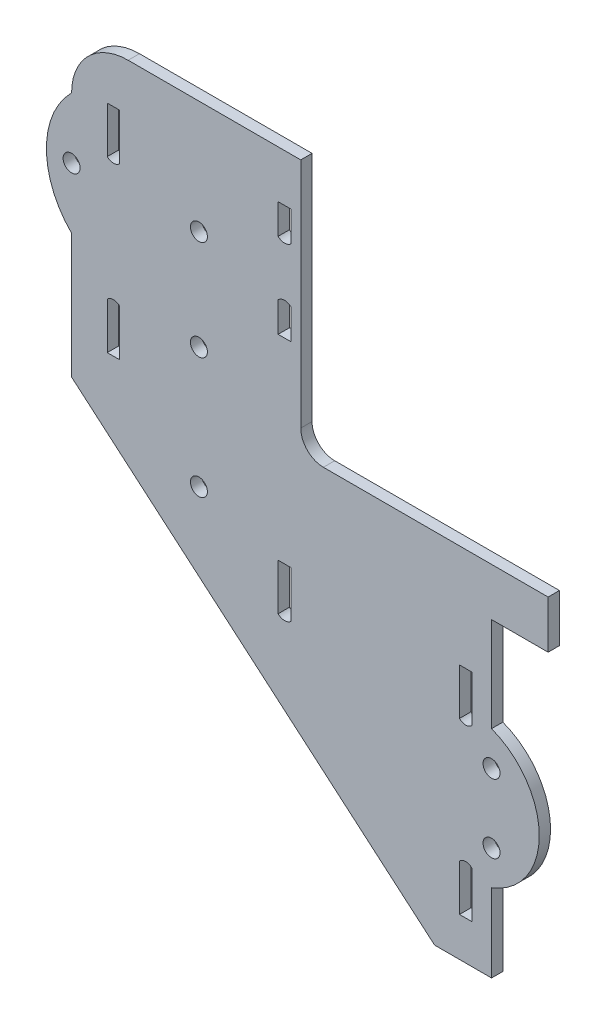
SolidWorks part; units mm, degrees
ref_plane "前视基准面" through (0, 0, 0) normal (0, 0, 1) x (1, 0, 0)
ref_plane "上视基准面" through (0, 0, 0) normal (0, 1, 0) x (1, 0, 0)
ref_plane "右视基准面" through (0, 0, 0) normal (1, 0, 0) x (0, 0, -1)
sketch "草图1" plane through (0, 0, 0) normal (0, 0, 1) x (1, 0, 0)
  line L1 (-9.5329, 8.949) -> (-7.3329, 8.949)
  line L3 (52.7171, -45.9251) -> (54.9171, -45.9251)
  line L4 (52.7171, -45.9251) -> (52.7171, -54.1251)
  line L5 (-9.5329, 8.949) -> (-9.5329, 0.749)
  line L6 (24.6671, 17.3485) -> (24.6671, -23.7015)
  line L8 (24.6671, 17.3485) -> (-5.8377, 17.3485) construction
  line L9 (20.6671, 3.799) -> (20.6671, 3.649) construction
  line L10 (20.8171, 3.799) -> (20.6671, 3.799) construction
  line L11 (22.8171, 8.949) -> (22.9671, 8.949) construction
  line L12 (22.8171, 8.799) -> (22.8171, 8.949) construction
  line L13 (20.8171, 3.799) -> (22.8171, 8.799) construction
  line L15 (-7.3329, 8.949) -> (-7.3329, 0.749)
  line L16 (-9.5329, 8.949) -> (-7.3329, 0.749) construction
  line L17 (-9.4329, 4.849) -> (-8.4329, 4.849)
  line L18 (-8.4329, 4.849) -> (-8.4329, -25.151) construction
  line L19 (-9.5329, 0.749) -> (-7.3329, 8.949) construction
  line L25 (-9.5329, -21.051) -> (-9.5329, -29.251)
  line L26 (-9.5329, -29.251) -> (-7.3329, -29.251)
  line L27 (-7.3329, -21.051) -> (-7.3329, -29.251)
  line L33 (20.6671, -11.201) -> (20.6671, -11.351) construction
  line L34 (20.8171, -11.201) -> (20.6671, -11.201) construction
  line L35 (22.8171, -6.051) -> (22.9671, -6.051) construction
  line L36 (22.8171, -6.201) -> (22.8171, -6.051) construction
  line L37 (22.8171, -11.201) -> (20.8171, -11.201) construction
  line L38 (20.8171, 3.799) -> (22.8171, 8.799) construction
  line L40 (54.9171, -45.9251) -> (54.9171, -54.1251)
  line L41 (52.7171, -45.9251) -> (54.9171, -54.1251) construction
  line L42 (20.8171, -11.201) -> (22.8171, -6.201) construction
  line L47 (22.8171, -11.201) -> (20.8171, -7.201) construction
  line L71 (22.9671, -11.351) -> (22.9671, -45.9251) construction
  line L72 (20.6671, 8.949) -> (20.6671, 3.649)
  line L78 (22.9671, 8.949) -> (22.9671, 3.649)
  line L82 (22.9671, 8.949) -> (20.6671, 8.949)
  line L85 (20.6671, -6.051) -> (20.6671, -11.351)
  line L86 (22.9671, -11.351) -> (20.6671, -11.351)
  line L87 (22.9671, -6.051) -> (22.9671, -11.351)
  line L147 (20.6671, -45.9251) -> (22.9671, -45.9251)
  line L149 (52.8171, -50.0251) -> (53.8171, -50.0251)
  line L150 (53.8171, -50.0251) -> (53.8171, -80.0251) construction
  line L151 (52.7171, -54.1251) -> (54.9171, -45.9251) construction
  line L155 (52.7171, -75.9251) -> (52.7171, -84.1251)
  line L156 (52.7171, -84.1251) -> (54.9171, -84.1251)
  line L157 (54.9171, -75.9251) -> (54.9171, -84.1251)
  line L158 (52.7171, -75.9251) -> (54.9171, -84.1251) construction
  line L159 (52.8171, -80.0251) -> (53.8171, -80.0251)
  line L160 (52.7171, -84.1251) -> (54.9171, -75.9251) construction
  line L161 (20.6671, -45.9251) -> (20.6671, -54.1251)
  line L175 (-15.8377, 7.3485) -> (-15.8377, -14.1323) construction
  line L177 (22.9671, -45.9251) -> (22.9671, -54.1251)
  line L178 (20.6671, -45.9251) -> (22.9671, -54.1251) construction
  line L181 (20.6671, -54.1251) -> (22.9671, -45.9251) construction
  line L187 (-5.8377, 17.3485) -> (24.6671, 17.3485)
  line L189 (-9.5329, -21.051) -> (-7.3329, -29.251) construction
  line L190 (-9.4329, -25.151) -> (-8.4329, -25.151)
  line L191 (-9.5329, -29.251) -> (-7.3329, -21.051) construction
  line L192 (20.6671, 8.949) -> (-7.3329, 8.949)
  line L200 (28.6671, -27.7015) -> (58.3856, -27.7015)
  line L202 (58.3856, -27.7015) -> (68.3856, -27.7015)
  line L205 (58.3856, -36.1516) -> (58.3856, -41.8372)
  line L209 (-15.8377, -14.1323) -> (-15.8377, -36.1516)
  line L210 (-15.8377, -36.1516) -> (48.3229, -91.0154)
  line L211 (48.3229, -91.0154) -> (58.3856, -91.0154)
  line L212 (53.8171, -65.0251) -> (77.8378, -65.0251) construction
  line L215 (58.3856, -41.8372) -> (58.3856, -52.8543)
  line L216 (58.3856, -91.0154) -> (58.3856, -77.1959)
  line L217 (58.3856, -52.8543) -> (58.3856, -65.0251) construction
  line L218 (58.3856, -65.0251) -> (58.3856, -77.1959) construction
  line L219 (20.6671, -6.051) -> (-7.3329, 0.749) construction
  line L220 (20.6671, -11.351) -> (-7.3329, -29.251) construction
  line L221 (-7.3329, -29.251) -> (20.6671, -54.1251) construction
  line L222 (68.3856, -27.7015) -> (68.3856, -36.1516)
  line L223 (68.3856, -36.1516) -> (58.3856, -36.1516)
  arc A1 (-15.8377, 7.3485) -> (-5.8377, 17.3485) centre (-5.8377, 7.3485) cw
  arc A3 (28.6671, -27.7015) -> (24.6671, -23.7015) centre (28.6671, -23.7015) cw
  arc A6 (58.3856, -77.1959) -> (58.3856, -52.8543) centre (53.8171, -65.0251) ccw
  circle A8 centre (58.3856, -58.9397) radius 1.5
  circle A9 centre (58.3856, -71.1105) radius 1.5
  circle A10 centre (6.6671, -2.651) radius 1.5
  circle A11 centre (6.6671, -20.301) radius 1.5
  circle A12 centre (6.6671, -41.688) radius 1.5
  arc A13 (52.7171, -54.1251) -> (54.9171, -54.1251) centre (53.8171, -53.0251) ccw
  arc A14 (52.7171, -75.9251) -> (54.9171, -75.9251) centre (53.8171, -77.0251) cw
  arc A15 (-9.5329, 0.749) -> (-7.3329, 0.749) centre (-8.4329, 1.849) ccw
  arc A16 (-9.5329, -21.051) -> (-7.3329, -21.051) centre (-8.4329, -22.151) cw
  arc A17 (20.6671, 3.649) -> (22.9671, 3.649) centre (21.8171, 4.799) ccw
  arc A18 (20.6671, -6.051) -> (22.9671, -6.051) centre (21.8171, -7.201) cw
  arc A19 (20.6671, -54.1251) -> (22.9671, -54.1251) centre (21.8171, -52.9751) ccw
  arc A20 (-15.8377, -14.1323) -> (-15.8377, 7.3485) centre (-5.0974, -3.3919) cw
  circle A21 centre (-15.8377, -3.3919) radius 1.5
  dimension "D1" = 4
  dimension "D2" = 10
extrude "凸台-拉伸1" add sketch "草图1" along normal blind 2
